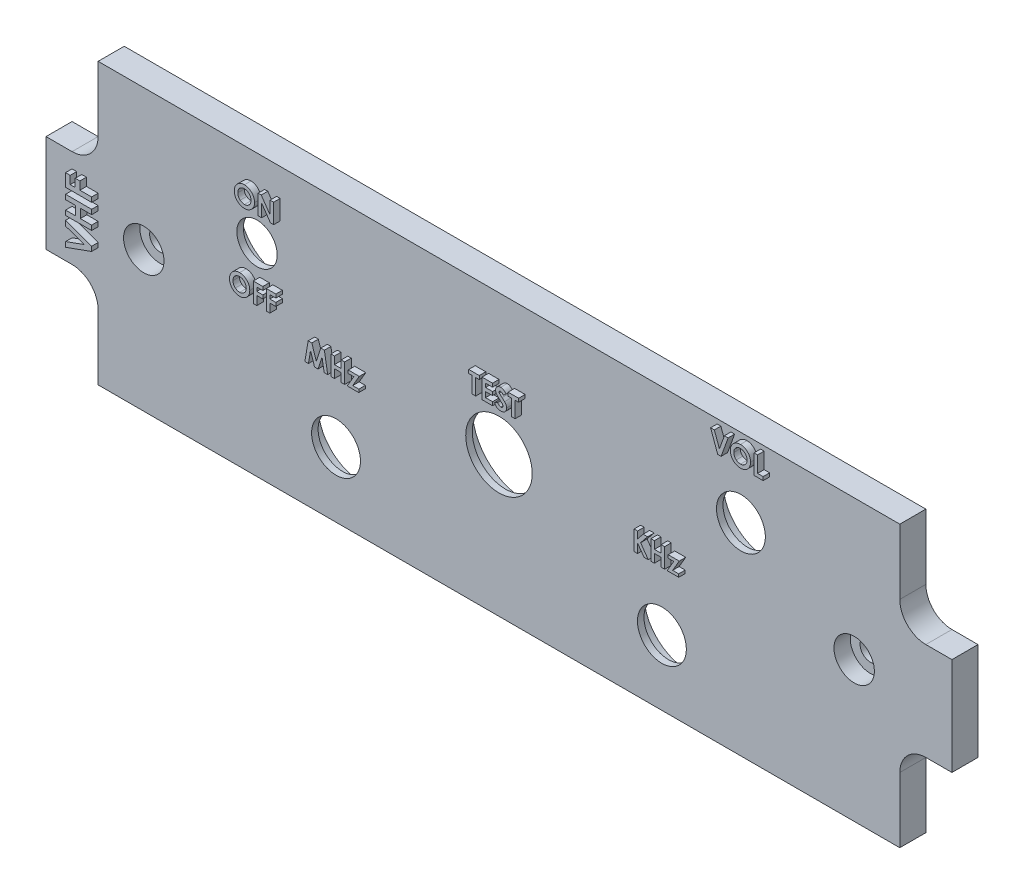
SolidWorks part; units mm, degrees
ref_plane "Front Plane" through (0, 0, 0) normal (0, 0, 1) x (1, 0, 0)
ref_plane "Top Plane" through (0, 0, 0) normal (0, 1, 0) x (1, 0, 0)
ref_plane "Right Plane" through (0, 0, 0) normal (1, 0, 0) x (0, 0, -1)
sketch "Sketch1" plane through (0, 0, 0) normal (0, 0, 1) x (1, 0, 0)
  line L0 (39.5, 10) -> (99.5, 10) construction
  line L1 (8, 0) -> (131, 0)
  line L2 (0, 14) -> (0, 29)
  line L3 (8, 43) -> (131, 43)
  line L4 (139, 14) -> (139, 29)
  line L5 (69.5, 43) -> (69.5, 0) construction
  line L13 (8, 43) -> (8, 33)
  line L14 (4, 29) -> (0, 29)
  line L15 (8, 0) -> (8, 10)
  line L16 (4, 14) -> (0, 14)
  line L17 (131, 43) -> (131, 33)
  line L18 (135, 29) -> (139, 29)
  line L19 (131, 0) -> (131, 10)
  line L20 (135, 14) -> (139, 14)
  line L21 (0, 21.5) -> (139, 21.5) construction
  line L22 (0, 0) -> (131, 0) construction
  line L23 (0, 0) -> (0, 64.6609) construction
  arc A8 (8, 10) -> (4, 14) centre (4, 10) ccw
  arc A9 (8, 33) -> (4, 29) centre (4, 33) cw
  arc A11 (131, 10) -> (135, 14) centre (135, 10) cw
  arc A12 (131, 33) -> (135, 29) centre (135, 33) ccw
  circle A26 centre (124, 21.5) radius 1.6 construction
  circle A27 centre (106.6244, 31) radius 3.75 construction
  circle A28 centre (94.5, 10) radius 3.75 construction
  circle A29 centre (69.5, 21.5) radius 5.1 construction
  circle A30 centre (44.5, 10) radius 3.75 construction
  circle A31 centre (32.3756, 31) radius 3.1 construction
  circle A32 centre (15, 21.5) radius 1.6 construction
  circle A33 centre (124, 21.5) radius 1.6
  circle A34 centre (106.6244, 31) radius 3.75
  circle A35 centre (94.5, 10) radius 3.75
  circle A36 centre (69.5, 21.5) radius 5.1
  circle A37 centre (44.5, 10) radius 3.75
  circle A38 centre (32.3756, 31) radius 3.1
  circle A39 centre (15, 21.5) radius 1.6
  point P13 (69.5, 10)
  point P21 (131, 14)
  point P25 (8, 29)
  point P40 (131, 29)
  dimension "D3" = 30
  dimension "D8" = 4
  dimension "D12" = 4
  dimension "D6" = 60
  dimension "D7" = 10
  dimension "D11" = 8
  dimension "D15" = 123
  dimension "D16" = 139
  dimension "D20" = 43
  dimension "D21" = 14
  dimension "D22" = 8
  dimension "D9" = 8
  dimension "D10" = 14
extrude "Boss-Extrude1" add sketch "Sketch1" along normal blind 4
sketch "Sketch2" plane through (0, 0, 0) normal (0, 0, -1) x (-1, 0, 0)
  circle A4 centre (-32.3756, 31) radius 6.7
  circle A16 centre (-32.3756, 31) radius 3.1 construction
  circle A17 centre (-44.5, 10) radius 3.75 construction
  circle A18 centre (-69.5, 21.5) radius 5.1 construction
  circle A19 centre (-94.5, 10) radius 3.75 construction
  circle A20 centre (-106.6244, 31) radius 3.75 construction
  circle A21 centre (-32.3756, 31) radius 3.1 construction
  circle A22 centre (-44.5, 10) radius 3.75 construction
  circle A23 centre (-69.5, 21.5) radius 5.1 construction
  circle A24 centre (-94.5, 10) radius 3.75 construction
  circle A25 centre (-106.6244, 31) radius 3.75 construction
  circle A27 centre (-44.5, 10) radius 6.75
  circle A28 centre (-69.5, 21.5) radius 8.1
  circle A29 centre (-94.5, 10) radius 6.75
  circle A30 centre (-106.6244, 31) radius 6.75
  dimension "D1" = 13.5
  dimension "D2" = 16.2
  dimension "D3" = 13.5
  dimension "D4" = 3.6
  dimension "D5" = 13.4
  dimension "D6" = 13.5
extrude "Back holes" cut sketch "Sketch2" against normal blind 3
sketch "Sketch3" plane through (0, 0, 4) normal (0, 0, 1) x (1, 0, 0)
  circle A2 centre (124, 21.5) radius 1.6 construction
  circle A3 centre (15, 21.5) radius 1.6 construction
  circle A6 centre (124, 21.5) radius 3.1
  circle A7 centre (15, 21.5) radius 3.1
  dimension "D1" = 1.5
extrude "Cama tornillos" cut sketch "Sketch3" against normal blind 2.5
sketch "Sketch4" plane through (0, 0, 4) normal (0, 0, 1) x (1, 0, 0)
  line L0 (8, 26.9631) -> (8, 14.5758) construction
  line L1 (8, 43) -> (8, 33) construction
  line L2 (33.1689, 19.9762) -> (113.2155, 19.9762) construction
  text T0 "<b>VHF</b>" font "Century Gothic" height 4
  text T1 "<b>OFF</b>" font "Century Gothic" height 3
  text T2 "<b>ON</b>\r\n" font "Century Gothic" height 3
  text T3 "<b>TEST</b>" font "Century Gothic" height 3
  text T4 "<b>VOL</b>" font "Century Gothic" height 3
  text T5 "<b>MHz</b>" font "Century Gothic" height 3
  text T6 "KHz" font "Century Gothic" height 3
extrude "Textos" add sketch "Sketch4" along normal blind 1
